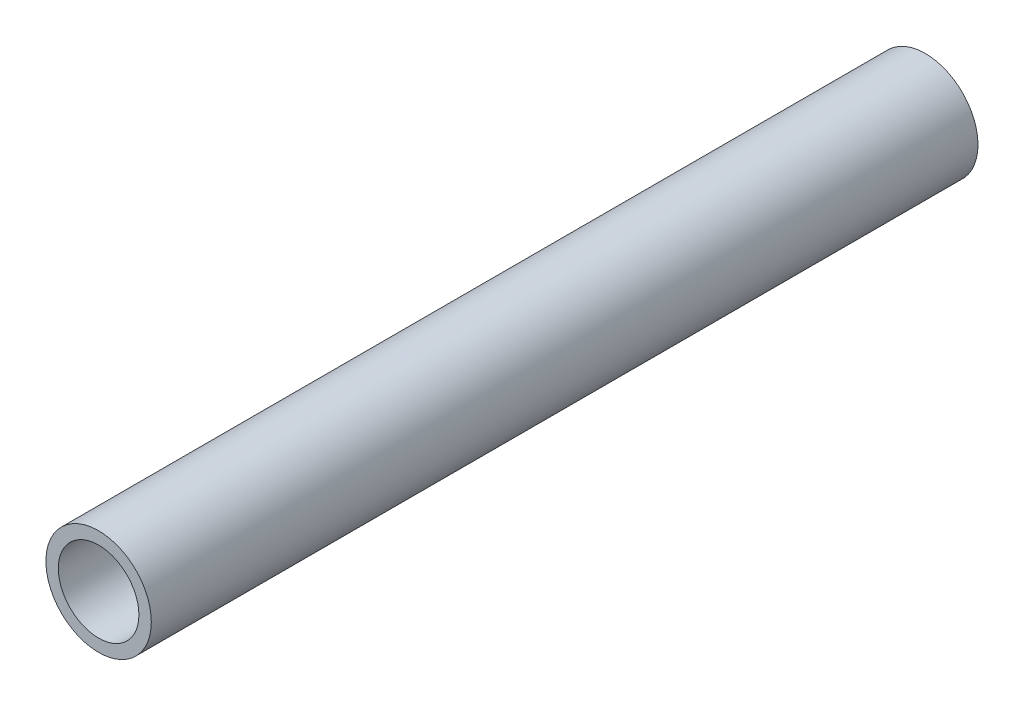
SolidWorks part; units mm, degrees
material "AISI 304"
ref_plane "Front Plane" through (0, 0, 0) normal (0, 0, 1) x (1, 0, 0)
ref_plane "Top Plane" through (0, 0, 0) normal (0, 1, 0) x (1, 0, 0)
ref_plane "Right Plane" through (0, 0, 0) normal (1, 0, 0) x (0, 0, -1)
sketch "Sketch1" plane through (0, 0, 0) normal (0, 0, 1) x (1, 0, 0)
  circle A0 centre (0, 0) radius 0.4953
  circle A1 centre (0, 0) radius 0.6477
  dimension "Needle Inner Diameter" = 0.9906
  dimension "Needle Outer Diameter" = 1.2954
extrude "Boss-Extrude1" add sketch "Sketch1" along normal blind 10.16
